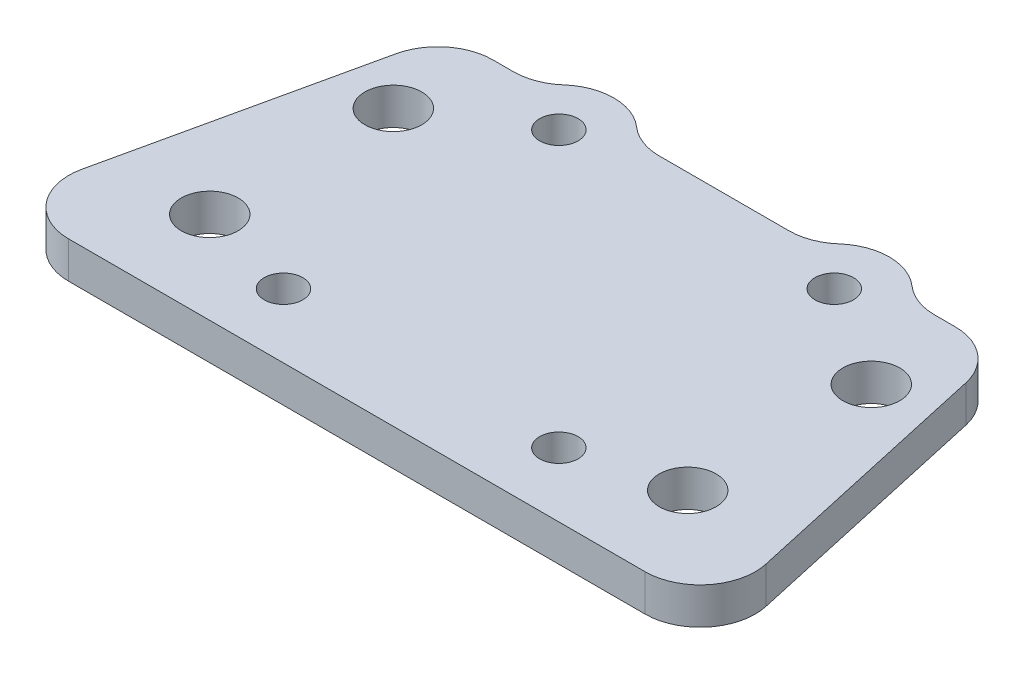
SolidWorks part; units mm, degrees
ref_plane "前视基准面" through (0, 0, 0) normal (0, 0, 1) x (1, 0, 0)
ref_plane "上视基准面" through (0, 0, 0) normal (0, 1, 0) x (1, 0, 0)
ref_plane "右视基准面" through (0, 0, 0) normal (1, 0, 0) x (0, 0, -1)
sketch "草图1" plane through (0, 0, 0) normal (0, 1, 0) x (1, 0, 0)
  line L0 (-10, 10) -> (-15, 10)
  line L1 (-10, -10) -> (10, -10)
  line L2 (-10, -10) -> (-10, 10)
  line L3 (-10, 10) -> (10, 10)
  line L4 (10, -10) -> (10, 10)
  line L5 (-10, -10) -> (10, 10) construction
  line L6 (-10, 10) -> (10, -10) construction
  line L7 (-15, 10) -> (-19.4377, -10)
  line L8 (-19.4377, -10) -> (-10, -10)
  line L9 (10, 10) -> (15, 10)
  line L10 (15, 10) -> (19.4377, -10)
  line L11 (19.4377, -10) -> (10, -10)
  point P0 (0, 0)
  dimension "D1" = 20
  dimension "D2" = 38.8754
  dimension "D3" = 5
  dimension "D4" = 20
extrude "凸台-拉伸1" add sketch "草图1" along normal blind 2
sketch "草图2" plane through (0, 2, 0) normal (0, 1, 0) x (1, 0, 0)
  line L0 (-13.018, 10) -> (-13.018, 5) construction
  line L1 (15, 10) -> (-15, 10) construction
  line L2 (-13.018, 5) -> (-13.018, -5) construction
  line L3 (-13.018, -5) -> (-13.018, -10) construction
  line L4 (-19.4377, -10) -> (19.4377, -10) construction
  line L5 (-13.018, 5) -> (-15.9644, 5.6537) construction
  line L6 (-15, 10) -> (-19.4377, -10) construction
  line L7 (-13.018, 5) -> (-10, 5) construction
  line L8 (-10, 5) -> (0, 5) construction
  line L9 (0, 5) -> (0, 0) construction
  circle A0 centre (-13.018, 5) radius 1.55
  circle A1 centre (-13.018, -5) radius 1.55
  circle A2 centre (13.018, -5) radius 1.55
  circle A3 centre (13.018, 5) radius 1.55
  dimension "D3" = 3.1
  dimension "D1" = 10
  dimension "D2" = 5
  dimension "D4" = 5
extrude "切除-拉伸1" cut sketch "草图2" against normal through all
sketch "草图3" plane through (0, 2, 0) normal (0, 1, 0) x (1, 0, 0)
  line L0 (0, 10) -> (0, -10) construction
  line L2 (-19.4377, -10) -> (19.4377, -10) construction
  line L4 (-7.5, -6.5) -> (7.5, -6.5) construction
  line L5 (-7.5, -6.5) -> (-7.5, 8.5) construction
  line L6 (-7.5, 8.5) -> (7.5, 8.5) construction
  line L7 (7.5, -6.5) -> (7.5, 8.5) construction
  line L8 (-7.5, -6.5) -> (7.5, 8.5) construction
  line L9 (-7.5, 8.5) -> (7.5, -6.5) construction
  line L10 (15, 10) -> (-15, 10) construction
  circle A0 centre (-7.5, 8.5) radius 1.05
  circle A1 centre (-7.5, -6.5) radius 1.05
  circle A2 centre (7.5, -6.5) radius 1.05
  circle A3 centre (7.5, 8.5) radius 1.05
  point P6 (0, 1)
  dimension "D3" = 2.1
  dimension "D1" = 15
  dimension "D2" = 3.5
extrude "切除-拉伸2" cut sketch "草图3" against normal through all
fillet "圆角2" radius 3 4 edges at (19.4377, 1, 10) (-19.4377, 1, 10) (-15, 1, -10) (15, 1, -10)
sketch "草图4" plane through (0, 2, 0) normal (0, 1, 0) x (1, 0, 0)
  line L0 (-10.0981, 10) -> (-4.9019, 10)
  line L1 (12.5927, 10) -> (-12.5927, 10) construction
  line L2 (4.9019, 10) -> (10.0981, 10)
  circle A0 centre (-7.5, 8.5) radius 3
  circle A1 centre (7.5, 8.5) radius 3
  line M15 (12.5927, 10) -> (-12.5927, 10)
  dimension "D1" = 6
extrude "凸台-拉伸2" add sketch "草图4" against normal up to surface (2 mm away) contours A0 M15 | A1 M15
fillet "圆角4" radius 3 4 edges at (4.9019, 1, -10) (10.0981, 1, -10) (-10.0981, 1, -10) (-4.9019, 1, -10)
